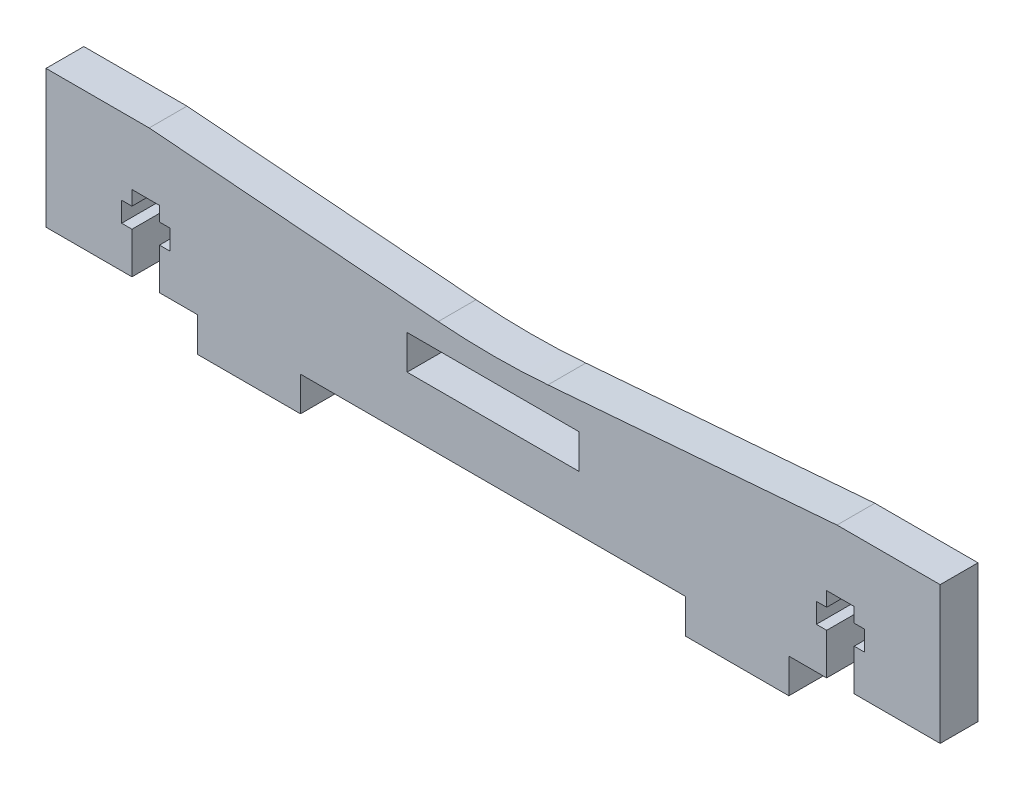
SolidWorks part; units mm, degrees
ref_plane "前视基准面" through (0, 0, 0) normal (0, 0, 1) x (1, 0, 0)
ref_plane "上视基准面" through (0, 0, 0) normal (0, 1, 0) x (1, 0, 0)
ref_plane "右视基准面" through (0, 0, 0) normal (1, 0, 0) x (0, 0, -1)
sketch "草图1" plane through (0, 0, 0) normal (0, 0, 1) x (1, 0, 0)
  line L0 (-65, 42.9879) -> (-65, -14.2658) construction
  line L1 (0, 0) -> (-130, 0)
  line L2 (0, 0) -> (0, 20)
  line L3 (0, 20) -> (-130, 20)
  line L4 (-130, 0) -> (-130, 20)
  line L5 (-117.5, 0) -> (-113.5, 0)
  line L6 (-108, 0) -> (-93, 0)
  line L7 (-108, 0) -> (-108, -5)
  line L8 (-108, -5) -> (-93, -5)
  line L9 (-93, 0) -> (-93, -5)
  line L10 (-37, 0) -> (-22, 0)
  line L11 (-37, 0) -> (-37, -5)
  line L12 (-37, -5) -> (-22, -5)
  line L13 (-22, 0) -> (-22, -5)
  line L14 (-117.5, 0) -> (-117.5, 11)
  line L15 (-117.5, 11) -> (-113.5, 11)
  line L16 (-113.5, 0) -> (-113.5, 11)
  line L17 (-119, 8.9) -> (-112, 8.9)
  line L18 (-119, 8.9) -> (-119, 6)
  line L19 (-119, 6) -> (-112, 6)
  line L20 (-112, 8.9) -> (-112, 6)
  line L21 (-18, 8.9) -> (-18, 6)
  line L22 (-11, 8.9) -> (-11, 6)
  line L23 (-12.5, 11) -> (-16.5, 11)
  line L24 (-16.5, 0) -> (-16.5, 11)
  line L25 (-11, 6) -> (-18, 6)
  line L26 (-11, 8.9) -> (-18, 8.9)
  line L27 (-12.5, 0) -> (-12.5, 11)
  line L28 (-115, 20) -> (-65, 16)
  line L29 (-65, 16) -> (-15, 20)
  line L31 (-77.5, 13) -> (-52.5, 13)
  line L32 (-77.5, 13) -> (-77.5, 8)
  line L33 (-77.5, 8) -> (-52.5, 8)
  line L34 (-52.5, 13) -> (-52.5, 8)
  point P23 (-119, 7.45)
  dimension "D1" = 130
  dimension "D2" = 20
  dimension "D3" = 65
  dimension "D4" = 5
  dimension "D5" = 5
  dimension "D6" = 15
  dimension "D7" = 15
  dimension "D8" = 28
  dimension "D9" = 28
  dimension "D10" = 7
  dimension "D11" = 2.9
  dimension "D12" = 1.5
  dimension "D13" = 11
  dimension "D14" = 0
  dimension "D15" = 6
  dimension "D16" = 5.5
  dimension "D17" = 4
  dimension "D18" = 15
  dimension "D19" = 15
  dimension "D20" = 4
  dimension "D21" = 5
  dimension "D22" = 25
  dimension "D23" = 12.5
  dimension "D24" = 8
extrude "凸台-拉伸1" add sketch "草图1" along normal blind 5.5 contours L0 L28 L3 L4 L1 L14 L19 L18 L17 L15 L16 L20 | L29 L0 L1 L24 L25 L21 L26 L23 L27 L22 L2 L3 | L13 L1 L11 L12 | L9 L1 L7 L8
fillet "圆角1" radius 100 1 edges at (-65, 16, 2.75)
